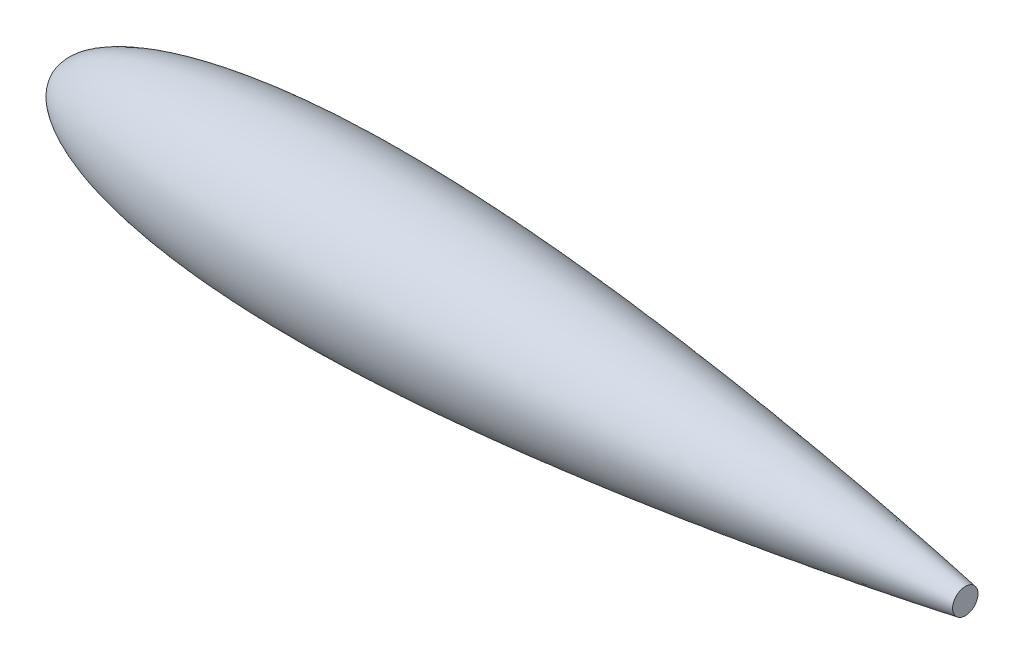
SolidWorks part; units mm, degrees
material "ASA Aero"
ref_plane "Front Plane" through (0, 0, 0) normal (0, 0, 1) x (1, 0, 0)
ref_plane "Top Plane" through (0, 0, 0) normal (0, 1, 0) x (1, 0, 0)
ref_plane "Right Plane" through (0, 0, 0) normal (1, 0, 0) x (0, 0, -1)
sketch "Sketch3" plane through (0, 0, 0) normal (0, 0, 1) x (1, 0, 0)
  line L0 (0, 0) -> (700, 0)
  spline S0 degree 4 poles (0, 0) (-0.0003, 0.8126) (0.0768, 2.1594) (0.3767, 4.0982) (1.1237, 6.6043) (2.1385, 8.9596) (3.6106, 11.5019) (5.6902, 14.2868) (8.6769, 17.4485) (13.0626, 21.1372) (19.6356, 25.4966) (29.4705, 30.5575) (44.5378, 36.4382) (66.5075, 42.6259) (92.5461, 47.5868) (121.2497, 51.2072) (156.9306, 54.0129) (197.423, 55.3566) (244.6849, 54.9357) (291.8934, 52.7739) (332.2993, 49.9825) (365.9296, 47.1336) (392.8086, 44.5756) (419.6624, 41.7662) (446.4912, 38.728) (473.2952, 35.4779) (500.0741, 32.0288) (523.4839, 28.8438) (543.5326, 25.9975) (560.2295, 23.548) (573.5786, 21.5421) (586.9236, 19.4887) (600.2557, 17.3889) (613.5897, 15.239) (626.8991, 13.043) (638.5643, 11.0724) (648.5145, 9.3592) (656.871, 7.8964) (663.4307, 6.7362) (670.2389, 5.5146) (676.5947, 4.3648) (683.7199, 3.054) (689.5339, 1.9779) (696.8743, 0.5949) (701.1789, -0.2229) (706.6896, -1.2795) (710.9307, -2.1005) (715.3544, -2.9633) (719.721, -3.8223) (724.1067, -4.6922) (728.4822, -5.5674) (733.9545, -6.6712) (740.516, -8.0097) (748.1682, -9.5931) (756.9062, -11.4326) (763.4553, -12.8356) (767.8187, -13.7815) (770, -14.2572) knots 0 0 0 0 0 0.00409 0.006806 0.009858 0.013162 0.016997 0.021592 0.027352 0.035055 0.045844 0.061296 0.083043 0.116515 0.160815 0.194864 0.228914 0.297013 0.365113 0.433212 0.467262 0.501312 0.535361 0.569411 0.603461 0.63751 0.67156 0.70561 0.722635 0.73966 0.756684 0.773709 0.790734 0.807759 0.824784 0.841809 0.850321 0.858833 0.867346 0.875858 0.884371 0.892883 0.901396 0.909908 0.915539 0.92117 0.9268 0.932431 0.938062 0.943693 0.949323 0.954954 0.966216 0.977477 0.988739 1 1 1 1 1 construction
  spline S1 degree 4 poles (0, 0) (-0.0003, 0.8126) (0.0768, 2.1594) (0.3767, 4.0982) (1.1237, 6.6043) (2.1385, 8.9596) (3.6106, 11.5019) (5.6902, 14.2868) (8.6769, 17.4485) (13.0626, 21.1372) (19.6356, 25.4966) (29.4705, 30.5575) (44.5378, 36.4382) (66.5075, 42.6259) (92.5461, 47.5868) (121.2497, 51.2072) (156.9306, 54.0129) (197.423, 55.3566) (244.6849, 54.9357) (291.8934, 52.7739) (332.2993, 49.9825) (365.9296, 47.1336) (392.8086, 44.5756) (419.6624, 41.7662) (446.4912, 38.728) (473.2952, 35.4779) (500.0741, 32.0288) (523.4839, 28.8438) (543.5326, 25.9975) (560.2295, 23.548) (573.5786, 21.5421) (586.9236, 19.4887) (600.2557, 17.3889) (613.5897, 15.239) (626.8991, 13.043) (638.5643, 11.0724) (648.5145, 9.3592) (656.871, 7.8964) (663.4307, 6.7362) (670.2389, 5.5146) (676.5947, 4.3648) (683.7199, 3.054) (689.5339, 1.9779) (695.5482, 0.8448) (698.4916, 0.2871) (700, 0) knots 0 0 0 0 0 0.00409 0.006806 0.009858 0.013162 0.016997 0.021592 0.027352 0.035055 0.045844 0.061296 0.083043 0.116515 0.160815 0.194864 0.228914 0.297013 0.365113 0.433212 0.467262 0.501312 0.535361 0.569411 0.603461 0.63751 0.67156 0.70561 0.722635 0.73966 0.756684 0.773709 0.790734 0.807759 0.824784 0.841809 0.850321 0.858833 0.867346 0.875858 0.884371 0.892883 0.901396 0.909908 0.909908 0.909908 0.909908 0.909908
revolve "Revolve1" add sketch "Sketch3" angle 360 about L0
sketch "Sketch5" plane through (0, 0, 0) normal (1, 0, 0) x (0, 0, -1)
  circle A0 centre (0, 0) radius 55
  dimension "D1" = 110
extrude "Cut-Extrude1" cut sketch "Sketch5" against normal blind 50 from offset 700
equation "\"tBar\"= \"maxDiameter\" / \"length\"'Max thickness of fuselage"
equation "\"maxDiameter\"= 110mm'Max diameter of fuselage"
equation "\"length\"= 700mm'Length of fuselage"
equation "\"D19@Cut-Extrude1\"=\"length\""
equation "\"kammback\"= 50mm'Length of cut from fuselage rear"
equation "\"D1@Cut-Extrude1\"=\"kammback\""
equation "\"tWall\"= 0.8mm'Thickness of fuselage wall"
equation "\"D1@Sketch5\"=\"maxDiameter\""
equation "\"tiltDiameter\"= 10mm'Diameter of holes for tiltrotor shaft"
equation "\"tiltY1\"= - 40mm'Y distance of front tiltrotor hole"
equation "\"tiltY2\"= \"tiltY1\"'Y distance of rear tiltrotor hole"
equation "\"tiltX1\"= 120mm'X distance of front tiltrotor"
equation "\"tiltX2\"= \"tiltX1\"'X distance of rear tiltrotor"
equation "\"X5\"= \"length\" / 3'X distance of main rotor"
equation "\"diameter5\"= 90mm'Diameter of main rotor"
